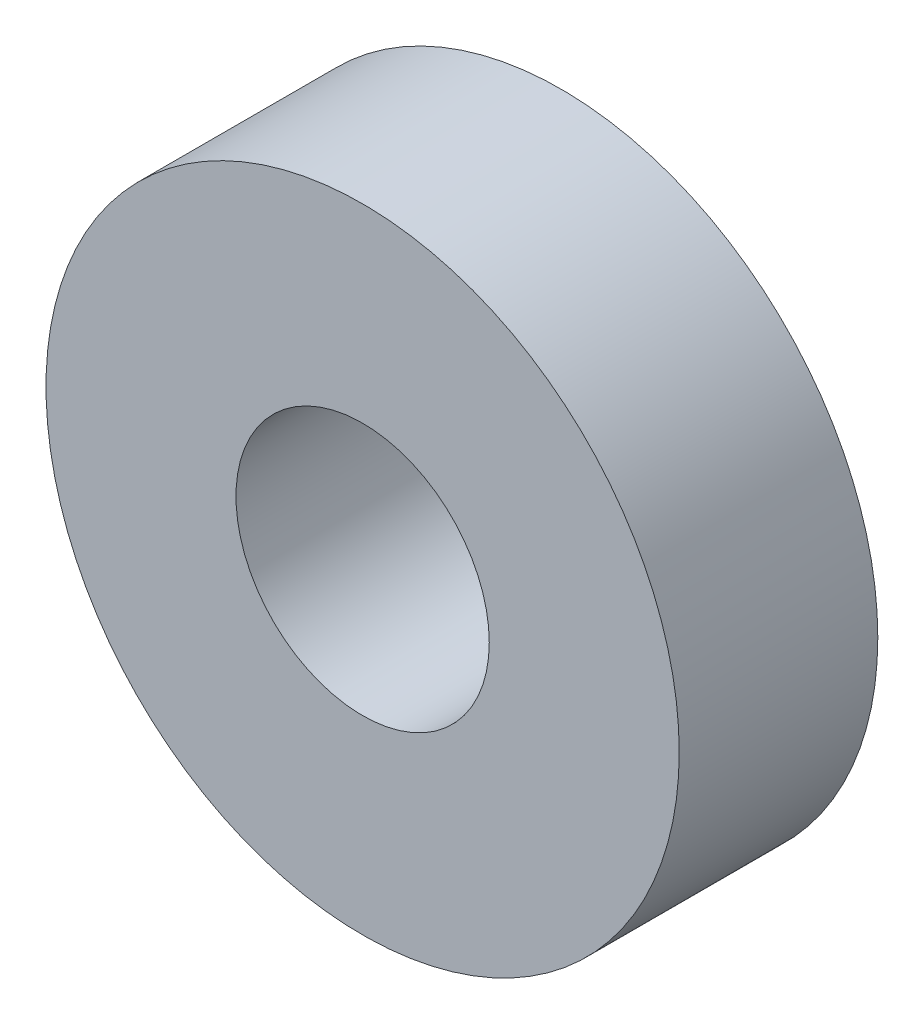
SolidWorks part; units mm, degrees
material "Chrome Stainless Steel"
ref_plane "Front Plane" through (0, 0, 0) normal (0, 0, 1) x (1, 0, 0)
ref_plane "Top Plane" through (0, 0, 0) normal (0, 1, 0) x (1, 0, 0)
ref_plane "Right Plane" through (0, 0, 0) normal (1, 0, 0) x (0, 0, -1)
sketch "Sketch1" plane through (0, 0, 0) normal (0, 0, 1) x (1, 0, 0)
  circle A0 centre (0, 0) radius 7.9375
  circle A1 centre (0, 0) radius 3.175
  dimension "D1" = 6.35
  dimension "D2" = 15.875
extrude "Boss-Extrude1" add sketch "Sketch1" along normal blind 4.9784
